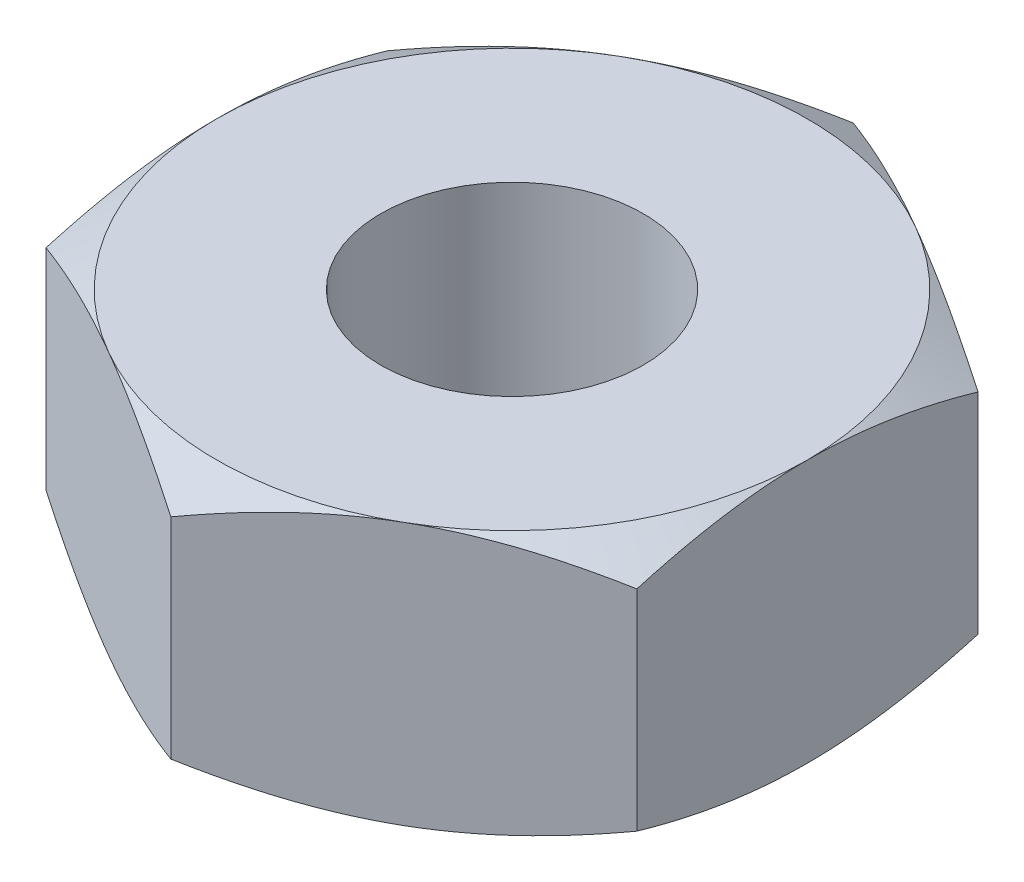
SolidWorks part; units mm, degrees
ref_plane "Front Plane" through (0, 0, 0) normal (0, 0, 1) x (1, 0, 0)
ref_plane "Top Plane" through (0, 0, 0) normal (0, 1, 0) x (1, 0, 0)
ref_plane "Right Plane" through (0, 0, 0) normal (1, 0, 0) x (0, 0, -1)
sketch "Sketch1" plane through (0, 0, 0) normal (0, 1, 0) x (1, 0, 0)
  line L1 (0, -2.5981) -> (2.25, -1.299)
  line L2 (2.25, -1.299) -> (2.25, 1.299)
  line L3 (2.25, 1.299) -> (0, 2.5981)
  line L4 (0, 2.5981) -> (-2.25, 1.299)
  line L5 (-2.25, 1.299) -> (-2.25, -1.299)
  line L6 (-2.25, -1.299) -> (0, -2.5981)
  circle A0 centre (0, 0) radius 2.25 construction
  circle A1 centre (0, 0) radius 1
  dimension "D1" = 4.5
  dimension "D2" = 2
extrude "Boss-Extrude1" add sketch "Sketch1" along normal blind 2
sketch "Sketch2" plane through (0, 2, 0) normal (0, 1, 0) x (1, 0, 0)
  circle A0 centre (0, 0) radius 2.25 construction
  circle A1 centre (0, 0) radius 2.25
extrude "Cut-Extrude1" cut sketch "Sketch2" against normal blind 2 draft 60 flip side to cut
sketch "Sketch3" plane through (0, 0, 0) normal (0, -1, 0) x (1, 0, 0)
  circle A0 centre (0, 0) radius 2.25 construction
  circle A1 centre (0, 0) radius 2.25
extrude "Cut-Extrude2" cut sketch "Sketch3" against normal blind 2 draft 60 flip side to cut
